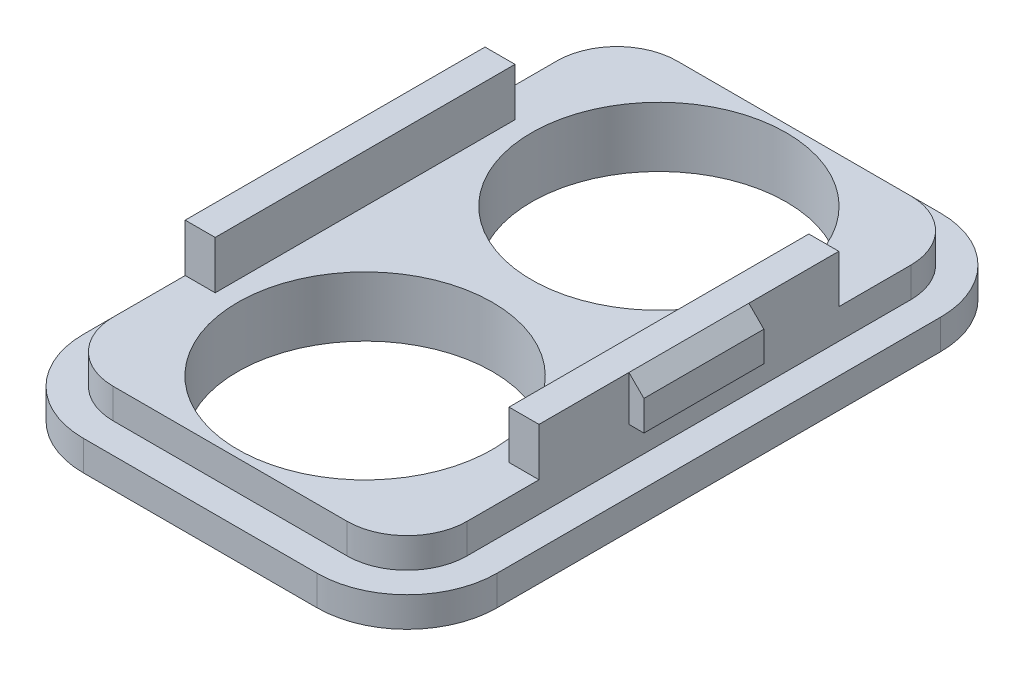
SolidWorks part; units mm, degrees
ref_plane "前视基准面" through (0, 0, 0) normal (0, 0, 1) x (1, 0, 0)
ref_plane "上视基准面" through (0, 0, 0) normal (0, 1, 0) x (1, 0, 0)
ref_plane "右视基准面" through (0, 0, 0) normal (1, 0, 0) x (0, 0, -1)
other "Configuration Table"
sketch "草图1" plane through (0, 0, 0) normal (0, 1, 0) x (1, 0, 0)
  line L1 (2, 0) -> (9.8, 0)
  line L2 (0, 2) -> (0, 16.8)
  line L3 (2, 18.8) -> (9.8, 18.8)
  line L4 (11.8, 2) -> (11.8, 16.8)
  line L5 (0, 0) -> (11.8, 18.8) construction
  line L6 (0, 18.8) -> (11.8, 0) construction
  arc A0 (0, 16.8) -> (2, 18.8) centre (2, 16.8) cw
  arc A1 (11.8, 16.8) -> (9.8, 18.8) centre (9.8, 16.8) ccw
  arc A2 (9.8, 0) -> (11.8, 2) centre (9.8, 2) ccw
  arc A3 (2, 0) -> (0, 2) centre (2, 2) cw
  point P4 (5.9, 9.4)
  dimension "D3" = 2
  dimension "D1" = 11.8
  dimension "D2" = 18.8
extrude "凸台-拉伸1" add sketch "草图1" along normal blind 1
sketch "草图2" plane through (0, 1, 0) normal (0, 1, 0) x (1, 0, 0)
  line L0 (0, 16.8) -> (0, 2) construction
  line L1 (0, 14.4) -> (1, 14.4)
  line L2 (0, 14.4) -> (0, 4.4)
  line L3 (0, 4.4) -> (1, 4.4)
  line L4 (1, 14.4) -> (1, 4.4)
  line L5 (0, 14.4) -> (1, 4.4) construction
  line L6 (0, 4.4) -> (1, 14.4) construction
  line L7 (5.9, 18.8) -> (5.9, 0) construction
  line L8 (9.8, 18.8) -> (2, 18.8) construction
  line L9 (2, 0) -> (9.8, 0) construction
  line L10 (0.5, 9.4) -> (5.9, 9.4) construction
  line L11 (11.8, 4.4) -> (10.8, 14.4) construction
  line L12 (11.8, 14.4) -> (10.8, 4.4) construction
  line L13 (10.8, 14.4) -> (10.8, 4.4)
  line L14 (11.8, 4.4) -> (10.8, 4.4)
  line L15 (11.8, 14.4) -> (11.8, 4.4)
  line L16 (11.8, 14.4) -> (10.8, 14.4)
  point P4 (0.5, 9.4)
  point P19 (11.3, 9.4)
  dimension "D1" = 10
  dimension "D2" = 1
extrude "凸台-拉伸2" add sketch "草图2" along normal blind 1.6
ref_plane "基准面1" through (0, 0, -9.4) normal (0, 0, 1) x (1, 0, 0)
sketch "草图3" plane through (0, 0, -9.4) normal (0, 0, 1) x (1, 0, 0)
  line L0 (0, 2.6) -> (0, 1.1)
  line L1 (0, 2.6) -> (0, 1) construction
  line L2 (0, 1.1) -> (-0.5, 1.1)
  line L3 (-0.5, 1.1) -> (-0.5, 2.1)
  line L4 (-0.5, 2.1) -> (0, 2.6)
  dimension "D1" = 135
  dimension "D2" = 0.5
  dimension "D3" = 1
extrude "凸台-拉伸3" add sketch "草图3" along normal blind 2 and the other way blind 2
sketch "草图4" plane through (0, 0, 0) normal (0, -1, 0) x (1, 0, 0)
  line L8 (2, -19.8) -> (9.8, -19.8)
  line L9 (12.8, -16.8) -> (12.8, -2)
  line L10 (9.8, 1) -> (2, 1)
  line L11 (-1, -2) -> (-1, -16.8)
  line L12 (2, -19.8) -> (9.8, -19.8)
  line L13 (12.8, -16.8) -> (12.8, -2)
  line L14 (9.8, 1) -> (2, 1)
  line L15 (-1, -2) -> (-1, -16.8)
  arc A8 (-1, -16.8) -> (2, -19.8) centre (2, -16.8) ccw
  arc A9 (9.8, -19.8) -> (12.8, -16.8) centre (9.8, -16.8) ccw
  arc A10 (12.8, -2) -> (9.8, 1) centre (9.8, -2) ccw
  arc A11 (2, 1) -> (-1, -2) centre (2, -2) ccw
  arc A12 (-1, -16.8) -> (2, -19.8) centre (2, -16.8) ccw
  arc A13 (9.8, -19.8) -> (12.8, -16.8) centre (9.8, -16.8) ccw
  arc A14 (12.8, -2) -> (9.8, 1) centre (9.8, -2) ccw
  arc A15 (2, 1) -> (-1, -2) centre (2, -2) ccw
  dimension "D1" = 1
extrude "凸台-拉伸4" add sketch "草图4" along normal blind 1
ref_plane "基准面2" through (5.9, 0, 0) normal (-1, 0, 0) x (0, 0, 1)
mirror "镜向1" about plane through (0, 0, -9.4) normal (0, 0, 1) of "凸台-拉伸3" second plane through (5.9, 0, 0) second plane normal (-1, 0, 0)
sketch "草图5" plane through (0, -1, 0) normal (0, -1, 0) x (1, 0, 0)
  circle A0 centre (5.9, -4.5) radius 4.25
  circle A1 centre (5.9, -14.3) radius 4.25
  dimension "D1" = 8.5
extrude "切除-拉伸1" cut sketch "草图5" against normal through all
